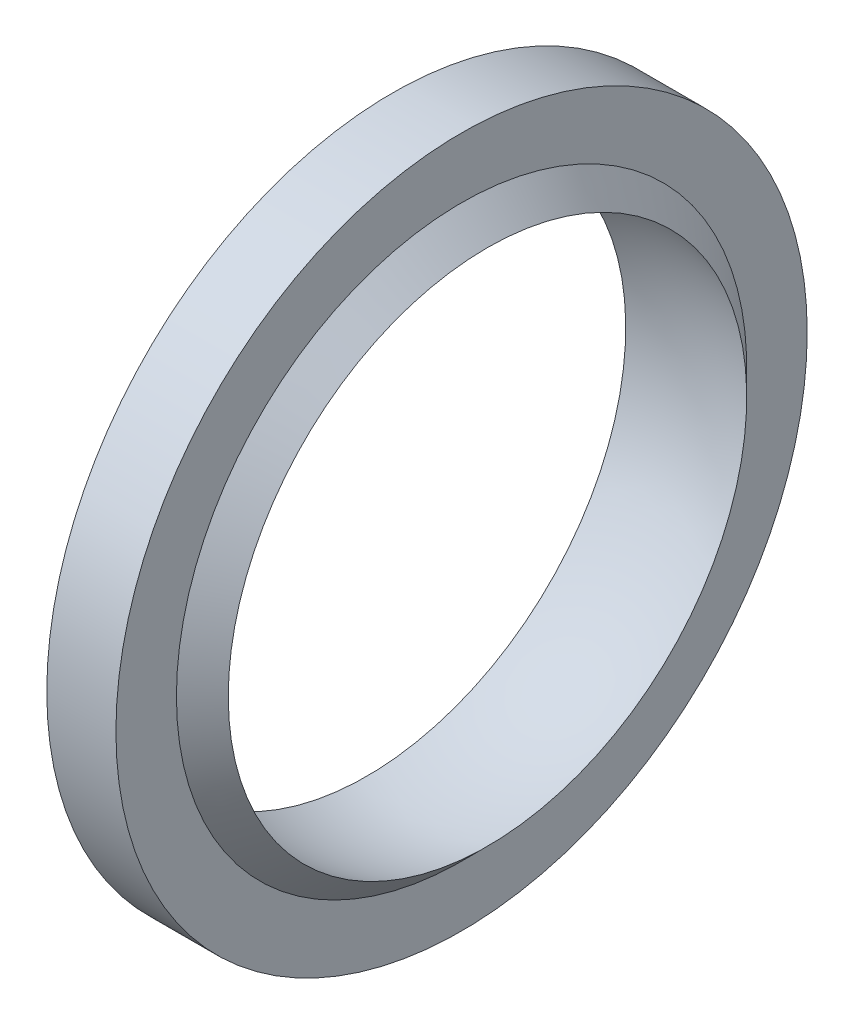
SolidWorks part; units mm, degrees
ref_plane "Plan1" through (0, 0, 0) normal (0, 0, 1) x (1, 0, 0)
ref_plane "Plan2" through (0, 0, 0) normal (0, 1, 0) x (1, 0, 0)
ref_plane "Plan3" through (0, 0, 0) normal (1, 0, 0) x (0, 0, -1)
sketch "Esquisse1" plane through (0, 0, 0) normal (0, 0, 1) x (1, 0, 0)
  line L0 (-2, 20) -> (2, 20)
  line L1 (2, 20) -> (2, 16.5)
  line L2 (2, 16.5) -> (3.5, 15)
  line L3 (-2, 20) -> (-2, 16.5)
  line L4 (-2, 16.5) -> (-3.5, 15)
  line L5 (0, 0) -> (14.9201, 0) construction
  arc A0 (-3.5, 15) -> (3.5, 15) centre (0, 0) cw
  dimension "D1" = 15
  dimension "D2" = 4
  dimension "D3" = 2
  dimension "D4" = 20
  dimension "D5" = 3.5
  dimension "D6" = 7
revolve "Base-Révolution" add sketch "Esquisse1" angle 360 about L5
